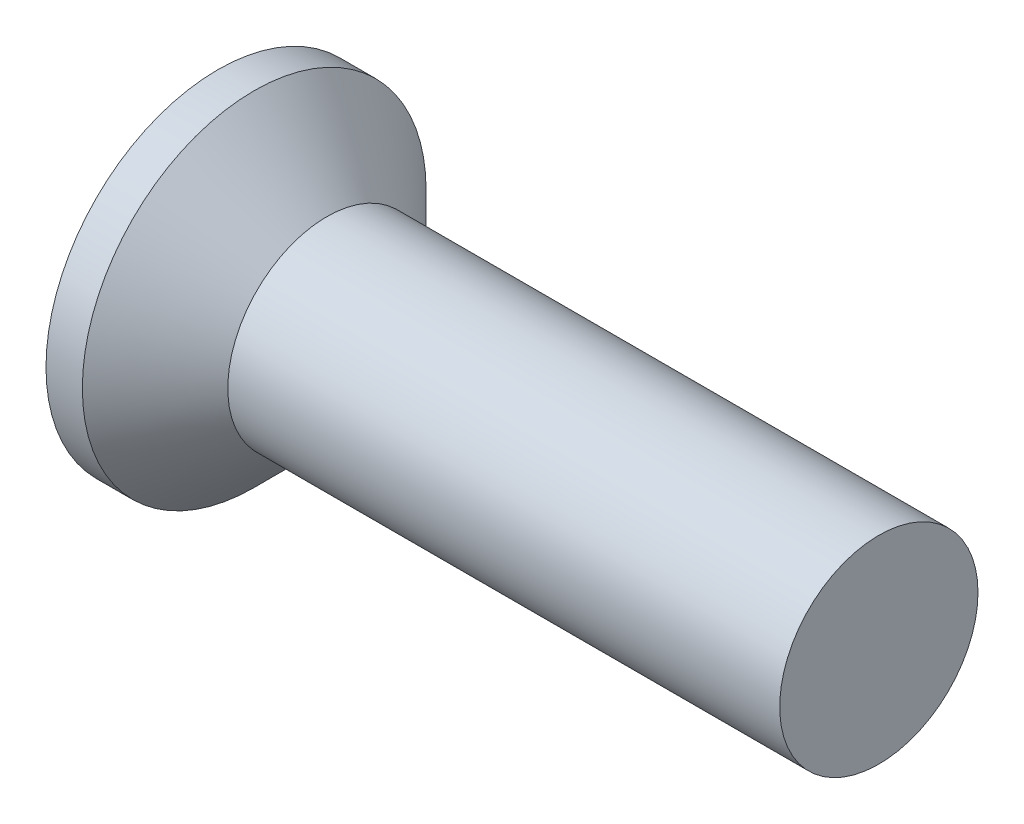
SolidWorks part; units mm, degrees
material "Q235-A"
ref_plane "Front" through (0, 0, 0) normal (0, 0, 1) x (1, 0, 0)
ref_plane "Top" through (0, 0, 0) normal (0, 1, 0) x (1, 0, 0)
ref_plane "Right" through (0, 0, 0) normal (1, 0, 0) x (0, 0, -1)
sketch "Sketch1" plane through (0, 0, 0) normal (0, 0, 1) x (1, 0, 0)
  line L0 (10, 1.5) -> (2.65, 1.5)
  line L1 (2.65, 1.5) -> (1.65, 1.5)
  line L2 (1.65, 1.5) -> (0.55, 2.6)
  line L3 (0.55, 2.6) -> (0, 2.6)
  line L4 (10, 1.5) -> (10, 0)
  line L5 (4.5158, 0) -> (-89.8219, 0) construction
  line L6 (10, 0) -> (0, 0)
  line L7 (0, 2.6) -> (0, 0)
  dimension "d" = 3
  dimension "D1" = 45
  dimension "dk" = 5.2
  dimension "k" = 1.65
  dimension "l" = 10
  dimension "a" = 1
revolve "Base" add sketch "Sketch1" angle 360 about L5
cosmetic thread "ThreadCosmetic1" [suppressed] parameters "bb"=8.35, "THD_MINOR"=2.459
cosmetic thread "装饰螺纹线1" parameters "D1"=5, "D2"=2
sketch "Sketch6" plane through (0, 0, 0) normal (1, 0, 0) x (0, 0, -1)
  line L0 (-1.9271, 0) -> (2.0512, 0) construction
  line L1 (0, 1.8651) -> (0, -2.0207) construction
  line L2 (0.32, 0.32) -> (0.32, 1.6)
  line L3 (0.32, 1.6) -> (-0.32, 1.6)
  line L4 (-0.32, 0.32) -> (-0.32, 1.6)
  line L5 (0.32, 0.32) -> (1.6, 0.32)
  line L6 (1.6, 0.32) -> (1.6, -0.32)
  line L7 (-1.6, 0.32) -> (-1.6, -0.32)
  line L8 (-0.32, 0.32) -> (-1.6, 0.32)
  line L9 (-0.32, -0.32) -> (-1.6, -0.32)
  line L10 (0.32, -0.32) -> (1.6, -0.32)
  line L11 (-0.32, -0.32) -> (-0.32, -1.6)
  line L12 (0.32, -1.6) -> (-0.32, -1.6)
  line L13 (0.32, -0.32) -> (0.32, -1.6)
  point P16 (-1.6, 0)
  point P17 (1.6, 0)
extrude "CrossRecess" cut sketch "Sketch6" along normal blind 0.825
draft "Draft9" type of draft neutral plane draft angle 30 faces to draft 4 face at (0.4125, 1.6, 0) face at (0.4125, 0, 1.6) face at (0.4125, -1.6, 0) face at (0.4125, 0, -1.6) neutral plane through (0, 2.6, 0) neutral plane normal (-1, 0, 0) parameters "D1"=30
fillet "Fillet5" radius 0.3 4 edges at (0.4125, -0.32, -0.32) (0.4125, 0.32, -0.32) (0.4125, 0.32, 0.32) (0.4125, -0.32, 0.32)
sketch "Sketch7" plane through (0, 0, 0) normal (1, 0, 0) x (0, 0, -1)
  line L0 (-2.0126, 0) -> (1.9757, 0) construction
  line L1 (0, 1.9314) -> (0, -2.0126) construction
  line L2 (0, 0) -> (1.5555, 1.5555) construction
  line L3 (0, 0.4782) -> (1.1314, 1.1314)
  line L4 (-1.5402, 1.5402) -> (0, 0) construction
  line L5 (0.4782, 0) -> (1.1314, 1.1314)
  line L6 (0, -0.4782) -> (1.1314, -1.1314)
  line L7 (0.4782, 0) -> (1.1314, -1.1314)
  line L8 (-0.4782, 0) -> (-1.1314, -1.1314)
  line L9 (0, -0.4782) -> (-1.1314, -1.1314)
  line L10 (-0.4782, 0) -> (-1.1314, 1.1314)
  line L11 (0, 0.4782) -> (-1.1314, 1.1314)
  dimension "D3" = 15
  dimension "m" = 3.2
extrude "Cut-Extrude3" [suppressed] cut sketch "Sketch7" along normal blind 10 draft 20
sketch "Sketch8" plane through (0, 0, 0) normal (0, 0, 1) x (1, 0, 0)
  line L0 (-15, 1.7705) -> (-16.25, 1.5)
  line L1 (-16.25, 1.5) -> (1.65, 1.5)
  line L3 (10, -1.5) -> (10, 1.5) construction
  line L6 (1.65, 1.5) -> (1.65, 6.5)
  line L7 (1.65, 6.5) -> (-15, 6.5)
  line L8 (-15, 6.5) -> (-15, 1.7705)
  line L9 (62.4753, 0.2705) -> (52.9594, 0.2705) construction
  dimension "D1" = 5
  dimension "x" = 1.25
  dimension "d" = 3
  dimension "THD_MINOR" = 2.459
  dimension "b" = 25
sketch "Sketch9" plane through (0, 0, 0) normal (0, 0, 1) x (1, 0, 0)
  line L0 (10, 1.2657) -> (10.1352, 1.5)
  line L1 (10.1352, 1.5) -> (10.1352, 1.7705)
  line L2 (10.1352, 1.7705) -> (9.8647, 1.7705)
  line L3 (9.8647, 1.7705) -> (9.8647, 1.5)
  line L4 (9.8647, 1.5) -> (10, 1.2657)
  line L5 (0, 0) -> (73.843, 0) construction
  line L6 (10, -1.5) -> (10, 1.5) construction
  dimension "D1" = 3
  dimension "D2" = 0.2705
revolve "Cut-Revolve10" [suppressed] cut sketch "Sketch9" angle 360 about L5
pattern_linear "LPattern10" [suppressed] count 26 spacing 0.3246 along (1, 0, 0)
equation "\"D1@Sketch6\" = \"m@Sketch6\" / 5"
equation "\"D1@CrossRecess\" = \"k@Sketch1\" / 2"
equation "\"D1@Sketch9\" = \"d@Sketch1\""
equation "\"D2@Sketch9\" =  ( \"d@Sketch1\" - \"THD_MINOR@ThreadCosmetic1\" )  / 2"
equation "\"D3@LPattern10\" = \"D2@Sketch9\" * 1.2"
equation "\"D1@LPattern10\" = \"bb@ThreadCosmetic1\" / \"D3@LPattern10\" "
